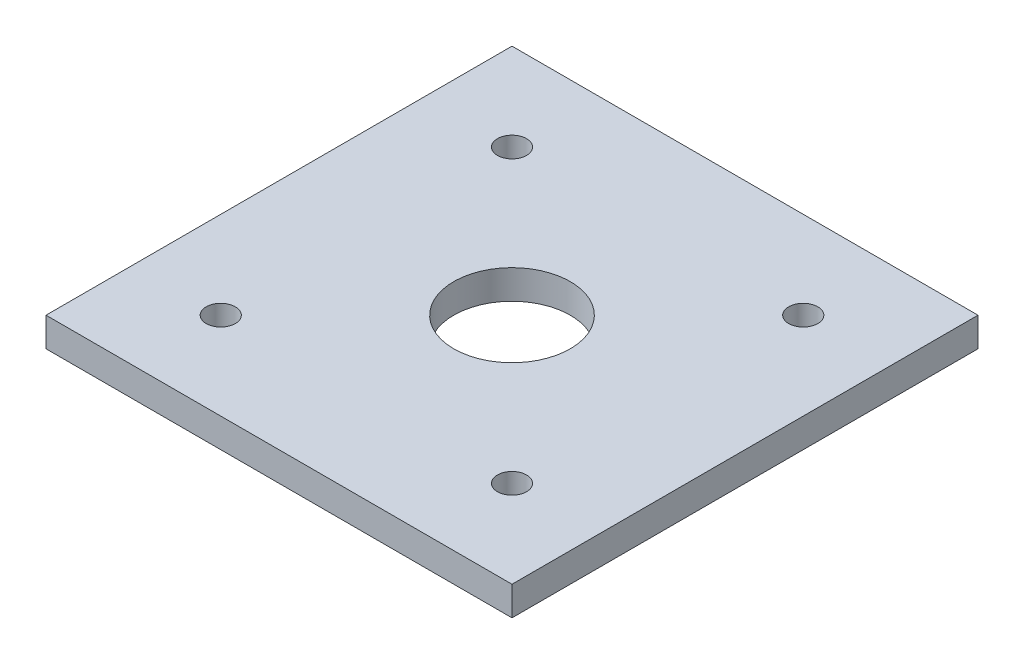
SolidWorks part; units mm, degrees
material "Galvanized Steel"
ref_plane "Front Plane" through (0, 0, 0) normal (0, 0, 1) x (1, 0, 0)
ref_plane "Top Plane" through (0, 0, 0) normal (0, 1, 0) x (1, 0, 0)
ref_plane "Right Plane" through (0, 0, 0) normal (1, 0, 0) x (0, 0, -1)
sketch "Sketch1" plane through (0, 0, 0) normal (0, 1, 0) x (1, 0, 0)
  line L1 (-50.8, 50.8) -> (50.8, 50.8)
  line L2 (-50.8, 50.8) -> (-50.8, -50.8)
  line L3 (-50.8, -50.8) -> (50.8, -50.8)
  line L4 (50.8, 50.8) -> (50.8, -50.8)
  line L5 (-50.8, 50.8) -> (50.8, -50.8) construction
  line L6 (-50.8, -50.8) -> (50.8, 50.8) construction
  circle A0 centre (0, 0) radius 12.7
  point P0 (0, 0)
  dimension "D2" = 25.4
  dimension "D1" = 101.6
extrude "Boss-Extrude1" add sketch "Sketch1" along normal blind 6.35
hole_wizard "1/4 (0.25) Diameter Hole1" positions "Sketch2" profile "Sketch3" hole size "1/4" standard "ANSI Inch" end condition through all
sketch "Sketch2" plane through (0, 6.35, 0) normal (0, 1, 0) x (1, 0, 0)
  line L0 (-50.8, 50.8) -> (-50.8, -50.8) construction
  line L1 (-50.8, -50.8) -> (50.8, -50.8) construction
  point P0 (-31.75, -31.75)
  dimension "D1" = 19.05
  dimension "D2" = 19.05
sketch "Sketch3" plane through (-31.75, 6.35, 31.75) normal (1, 0, 0) x (0, 0, 1)
  line L0 (0, 0) -> (0, 6.35)
  line L1 (0, 6.35) -> (3.175, 6.35)
  line L2 (3.175, 6.35) -> (3.175, 0)
  line L5 (3.175, 0) -> (0, 0)
  line L11 (0, -6.35) -> (0, 107.95) construction
  dimension "Thru Hole Dia." = 6.35
  dimension "Thru Hole Depth" = 6.35
pattern_circular "CirPattern1" count 4 over 360 about axis through (0, 0, 0) along (0, 1, 0) of "1/4 (0.25) Diameter Hole1"
